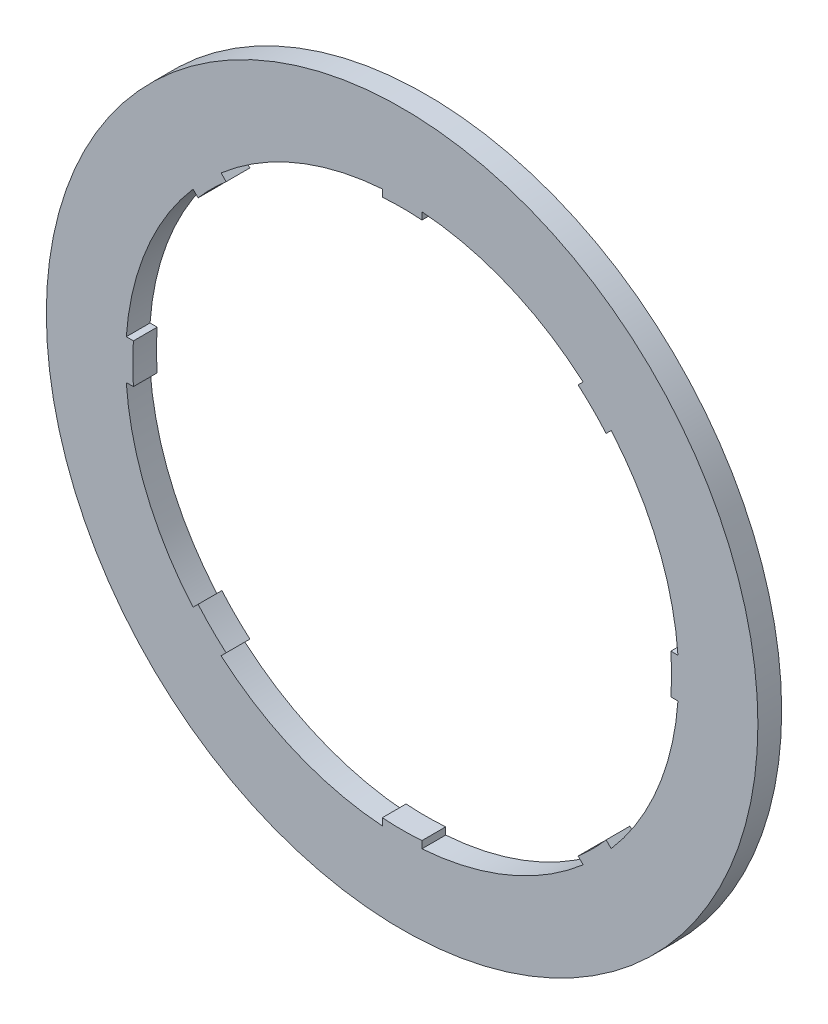
SolidWorks part; units mm, degrees
ref_plane "Alzado" through (0, 0, 0) normal (0, 0, 1) x (1, 0, 0)
ref_plane "Planta" through (0, 0, 0) normal (0, 1, 0) x (1, 0, 0)
ref_plane "Vista lateral" through (0, 0, 0) normal (1, 0, 0) x (0, 0, -1)
sketch "Croquis1" plane through (0, 0, 0) normal (0, 0, 1) x (1, 0, 0)
  line L0 (-34, 0) -> (34, 0) construction
  line L1 (0, 34) -> (0, -34) construction
  line L2 (-2.5, 33.908) -> (-2.5, 34.8103)
  line L3 (2.5, 33.908) -> (2.5, 34.8103)
  line L4 (2.5, -33.908) -> (2.5, -34.8103)
  line L5 (-2.5, -33.908) -> (-2.5, -34.8103)
  line L6 (-34.8103, 2.5) -> (-33.908, 2.5)
  line L7 (-33.908, -2.5) -> (-34.8103, -2.5)
  line L8 (34.8103, 2.5) -> (33.908, 2.5)
  line L9 (33.908, -2.5) -> (34.8103, -2.5)
  line L10 (-26.3824, 22.8469) -> (-25.7443, 22.2088)
  line L11 (-22.8469, 26.3824) -> (-22.2088, 25.7443)
  line L12 (0, 0) -> (-24.678, 24.678) construction
  line L13 (0, 0) -> (24.678, -24.678) construction
  line L14 (24.678, 24.678) -> (0, 0) construction
  line L15 (0, 0) -> (-24.2538, -24.2538) construction
  line L16 (26.3824, -22.8469) -> (25.7443, -22.2088)
  line L17 (22.8469, -26.3824) -> (22.2088, -25.7443)
  line L18 (22.8469, 26.3824) -> (22.2088, 25.7443)
  line L19 (26.3824, 22.8469) -> (25.7443, 22.2088)
  line L20 (-22.8469, -26.3824) -> (-22.2088, -25.7443)
  line L21 (-26.3824, -22.8469) -> (-25.7443, -22.2088)
  arc A0 (-22.2088, 25.7443) -> (-25.7443, 22.2088) centre (0, 0) ccw
  arc A1 (-34.8103, -2.5) -> (-26.3824, -22.8469) centre (0, 0) ccw
  circle A2 centre (0, 0) radius 44.9
  arc A3 (2.5, 33.908) -> (-2.5, 33.908) centre (0, 0) ccw
  arc A4 (25.7443, 22.2088) -> (22.2088, 25.7443) centre (0, 0) ccw
  arc A5 (33.908, -2.5) -> (33.908, 2.5) centre (0, 0) ccw
  arc A6 (22.2088, -25.7443) -> (25.7443, -22.2088) centre (0, 0) ccw
  arc A7 (-2.5, -33.908) -> (2.5, -33.908) centre (0, 0) ccw
  arc A8 (-25.7443, -22.2088) -> (-22.2088, -25.7443) centre (0, 0) ccw
  arc A9 (-33.908, 2.5) -> (-33.908, -2.5) centre (0, 0) ccw
  arc A10 (-26.3824, 22.8469) -> (-34.8103, 2.5) centre (0, 0) ccw
  arc A11 (-2.5, 34.8103) -> (-22.8469, 26.3824) centre (0, 0) ccw
  arc A12 (22.8469, 26.3824) -> (2.5, 34.8103) centre (0, 0) ccw
  arc A13 (34.8103, 2.5) -> (26.3824, 22.8469) centre (0, 0) ccw
  arc A14 (2.5, -34.8103) -> (22.8469, -26.3824) centre (0, 0) ccw
  arc A15 (26.3824, -22.8469) -> (34.8103, -2.5) centre (0, 0) ccw
  arc A16 (-22.8469, -26.3824) -> (-2.5, -34.8103) centre (0, 0) ccw
  dimension "D1" = 68
  dimension "D2" = 69.8
  dimension "D14" = 10
  dimension "D3" = 2.5
  dimension "D4" = 2.5
  dimension "D5" = 2.5
  dimension "D6" = 2.5
  dimension "D7" = 45
  dimension "D8" = 45
  dimension "D9" = 2.5
  dimension "D10" = 2.5
  dimension "D11" = 45
  dimension "D12" = 2.5
  dimension "D13" = 2.5
extrude "Saliente-Extruir1" add sketch "Croquis1" along normal blind 3
